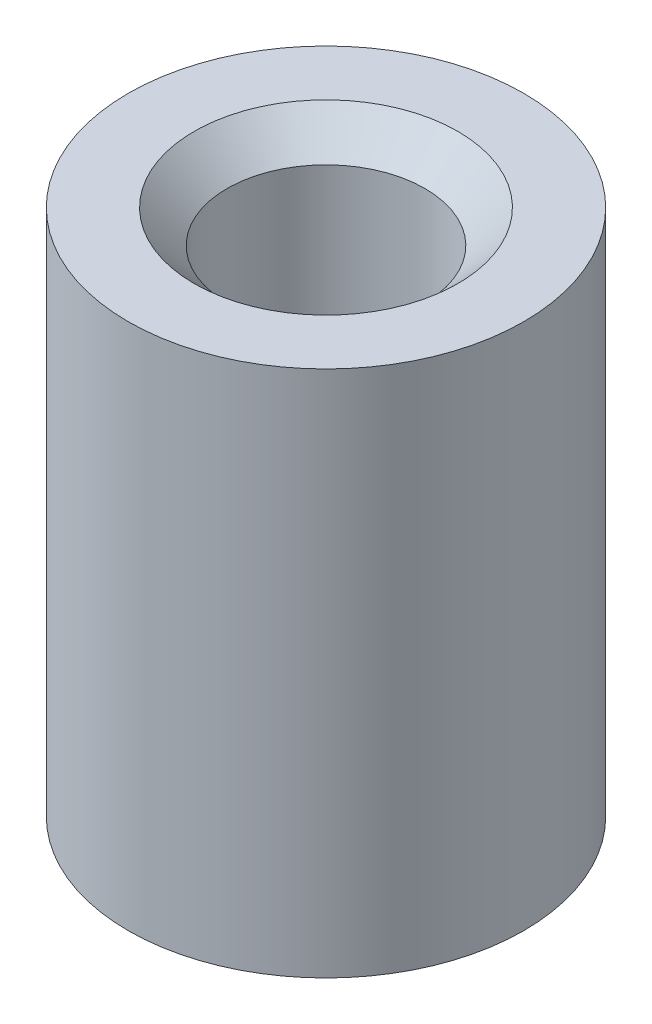
SolidWorks part; units mm, degrees
ref_plane "Front Plane" through (0, 0, 0) normal (0, 0, 1) x (1, 0, 0)
ref_plane "Top Plane" through (0, 0, 0) normal (0, 1, 0) x (1, 0, 0)
ref_plane "Right Plane" through (0, 0, 0) normal (1, 0, 0) x (0, 0, -1)
sketch "Sketch1" plane through (0, 0, 0) normal (0, 0, 1) x (1, 0, 0)
  line L0 (0, 0) -> (0, 16) construction
  line L1 (0, 16) -> (6, 16)
  line L2 (6, 16) -> (6, 0)
  line L3 (6, 0) -> (0, 0)
  line L4 (3, 16) -> (3, 0)
  dimension "D1" = 16
  dimension "D2" = 12
  dimension "D3" = 6
revolve "Revolve1" add sketch "Sketch1" angle 360 about L0
chamfer "Chamfer1" distance 1 angle 45 1 edges at (0, 16, -3)
